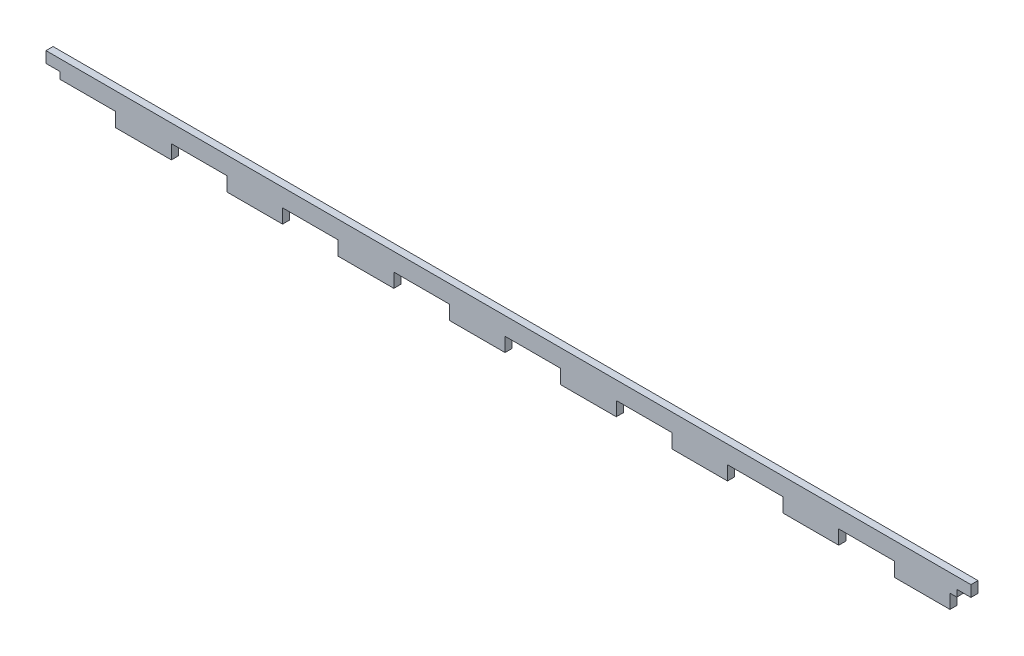
SolidWorks part; units mm, degrees
ref_plane "Front Plane" through (0, 0, 0) normal (0, 0, 1) x (1, 0, 0)
ref_plane "Top Plane" through (0, 0, 0) normal (0, 1, 0) x (1, 0, 0)
ref_plane "Right Plane" through (0, 0, 0) normal (1, 0, 0) x (0, 0, -1)
sketch "Sketch1" plane through (0, 0, 0) normal (0, 0, 1) x (1, 0, 0)
  line L0 (0, 0) -> (6.35, 0)
  line L2 (0, 0) -> (0, 5)
  line L3 (0, 5) -> (409.42, 5)
  line L6 (6.35, 0) -> (6.35, -3.03)
  line L7 (6.35, -3.03) -> (31.35, -3.03)
  line L8 (31.35, -3.03) -> (31.35, -9.38)
  line L9 (31.35, -9.38) -> (56.35, -9.38)
  line L10 (56.35, -9.38) -> (56.35, -3.03)
  line L11 (56.35, -3.03) -> (81.35, -3.03)
  line L12 (81.35, -3.03) -> (81.35, -9.38)
  line L13 (81.35, -9.38) -> (106.35, -9.38)
  line L14 (106.35, -9.38) -> (106.35, -3.03)
  line L15 (106.35, -3.03) -> (131.35, -3.03)
  line L16 (131.35, -3.03) -> (131.35, -9.38)
  line L17 (131.35, -9.38) -> (156.35, -9.38)
  line L18 (156.35, -9.38) -> (156.35, -3.03)
  line L19 (156.35, -3.03) -> (181.35, -3.03)
  line L20 (181.35, -3.03) -> (181.35, -9.38)
  line L21 (181.35, -9.38) -> (206.35, -9.38)
  line L22 (206.35, -9.38) -> (206.35, -3.03)
  line L23 (206.35, -3.03) -> (231.35, -3.03)
  line L24 (231.35, -3.03) -> (231.35, -9.38)
  line L25 (231.35, -9.38) -> (256.35, -9.38)
  line L26 (256.35, -9.38) -> (256.35, -3.03)
  line L27 (256.35, -3.03) -> (281.35, -3.03)
  line L28 (281.35, -3.03) -> (281.35, -9.38)
  line L29 (281.35, -9.38) -> (306.35, -9.38)
  line L30 (306.35, -9.38) -> (306.35, -3.03)
  line L31 (306.35, -3.03) -> (331.35, -3.03)
  line L32 (331.35, -3.03) -> (331.35, -9.38)
  line L33 (331.35, -9.38) -> (356.35, -9.38)
  line L34 (356.35, -9.38) -> (356.35, -3.03)
  line L35 (356.35, -3.03) -> (381.35, -3.03)
  line L36 (381.35, -3.03) -> (381.35, -9.38)
  line L37 (381.35, -9.38) -> (406.35, -9.38)
  line L38 (406.35, -9.38) -> (406.35, -3.03)
  line L41 (406.35, -3.03) -> (409.425, -3.0287)
  line L45 (415.775, 0) -> (415.775, 5)
  line L46 (415.775, 5) -> (409.42, 5)
  line L47 (415.775, 0) -> (409.425, 0)
  line L48 (409.425, 0) -> (409.425, -3.0287)
  dimension "D1" = 409.42
  dimension "D2" = 5
  dimension "D3" = 6.35
  dimension "D4" = 6.35
  dimension "D5" = 3.03
  dimension "D6" = 25
  dimension "D7" = 6.35
  dimension "D8" = 8
extrude "Boss-Extrude1" add sketch "Sketch1" along normal blind 3.175
